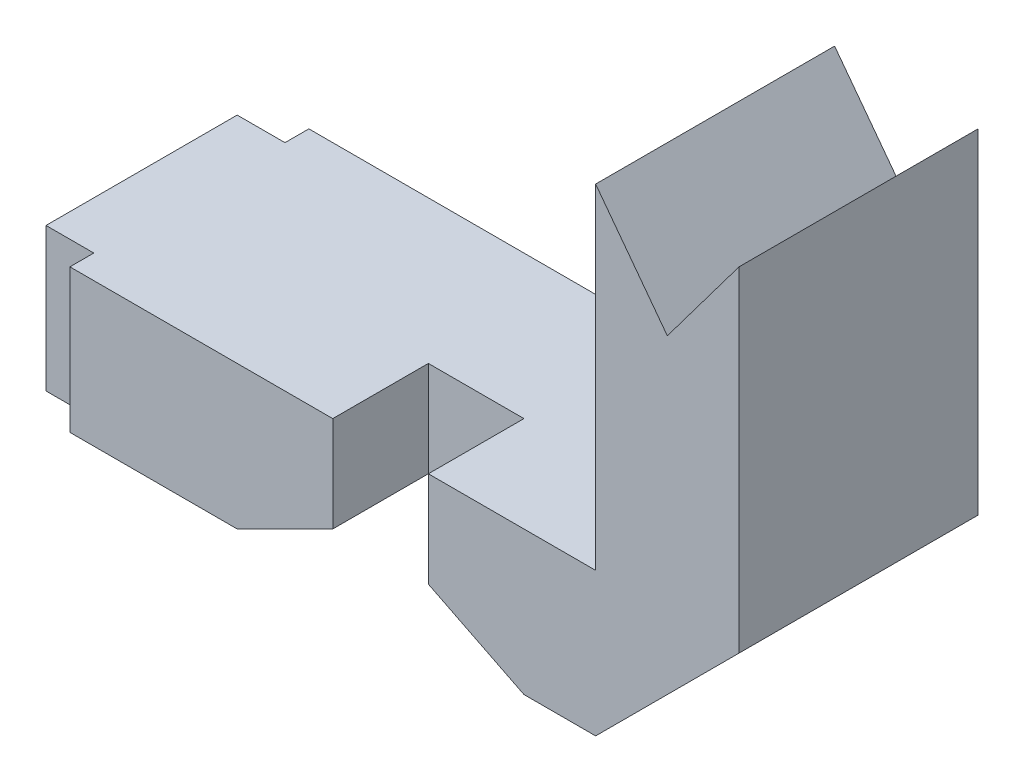
SolidWorks part; units mm, degrees
ref_plane "Спереди" through (0, 0, 0) normal (0, 0, 1) x (1, 0, 0)
ref_plane "Сверху" through (0, 0, 0) normal (0, 1, 0) x (1, 0, 0)
ref_plane "Справа" through (0, 0, 0) normal (1, 0, 0) x (0, 0, -1)
sketch "Эскиз1" plane through (0, 0, 0) normal (0, 0, 1) x (1, 0, 0)
  line L0 (-150, 0) -> (-30, 0)
  line L2 (-150, 0) -> (-150, -30)
  line L3 (-150, -30) -> (-30, -30)
  line L4 (0, 70) -> (0, 0)
  line L5 (-30, 0) -> (-30, 70)
  line L6 (-30, 70) -> (-15, 50)
  line L7 (-15, 50) -> (0, 70)
  line L8 (0, 0) -> (-30, -30)
  line L9 (-105, -30) -> (-85, -20)
  line L10 (-85, -20) -> (-65, -30)
  line L11 (-105, -30) -> (-65, -30)
  dimension "D1" = 120
  dimension "D2" = 30
  dimension "D3" = 30
  dimension "D4" = 30
  dimension "D5" = 20
  dimension "D6" = 70
  dimension "D7" = 70
  dimension "D8" = 25
  dimension "D9" = 120
  dimension "D10" = 20
  dimension "D11" = 20
  dimension "D12" = 10
  dimension "D13" = 45
extrude "Бобышка-Вытянуть1" add sketch "Эскиз1" along normal blind 50 contours L4 L8 L3 L2 L0 L5 L6 L7
sketch "Эскиз2" plane through (0, 0, 50) normal (0, 0, 1) x (1, 0, 0)
  line L0 (-105, -30) -> (-75, -15)
  line L1 (-150, -30) -> (-30, -30) construction
  line L2 (-75, -15) -> (-45, -30)
  line L4 (-105, -30) -> (-45, -30)
  dimension "D1" = 60
  dimension "D2" = 30
  dimension "D3" = 15
  dimension "D4" = 45
extrude "Вырез-Вытянуть1" cut sketch "Эскиз2" against normal through all
sketch "Эскиз3" plane through (0, 0, 50) normal (0, 0, 1) x (1, 0, 0)
  line L0 (-150, 0) -> (-30, 0) construction
  line L1 (-85, 0) -> (-65, 0)
  line L2 (-85, 0) -> (-85, -20)
  line L3 (-85, -20) -> (-65, -20)
  line L4 (-65, 0) -> (-65, -20)
  dimension "D1" = 20
  dimension "D2" = 20
  dimension "D3" = 20
extrude "Вырез-Вытянуть2" cut sketch "Эскиз3" against normal blind 20
sketch "Эскиз5" plane through (0, 0, 0) normal (0, 1, 0) x (1, 0, 0)
  line L0 (-150, -25) -> (-65.0083, -25) construction
  line L1 (-150, -50) -> (-150, 0) construction
  line L2 (-140, 0) -> (-140, -5)
  line L3 (-150, -50) -> (-140, -50)
  line L4 (-150, -50) -> (-150, -45)
  line L5 (-150, -45) -> (-140, -45)
  line L6 (-140, -50) -> (-140, -45)
  line L7 (-150, -5) -> (-140, -5)
  line L8 (-150, 0) -> (-150, -5)
  line L9 (-150, 0) -> (-140, 0)
  dimension "D1" = 5
  dimension "D2" = 10
extrude "Вырез-Вытянуть3" cut sketch "Эскиз5" against normal through all
